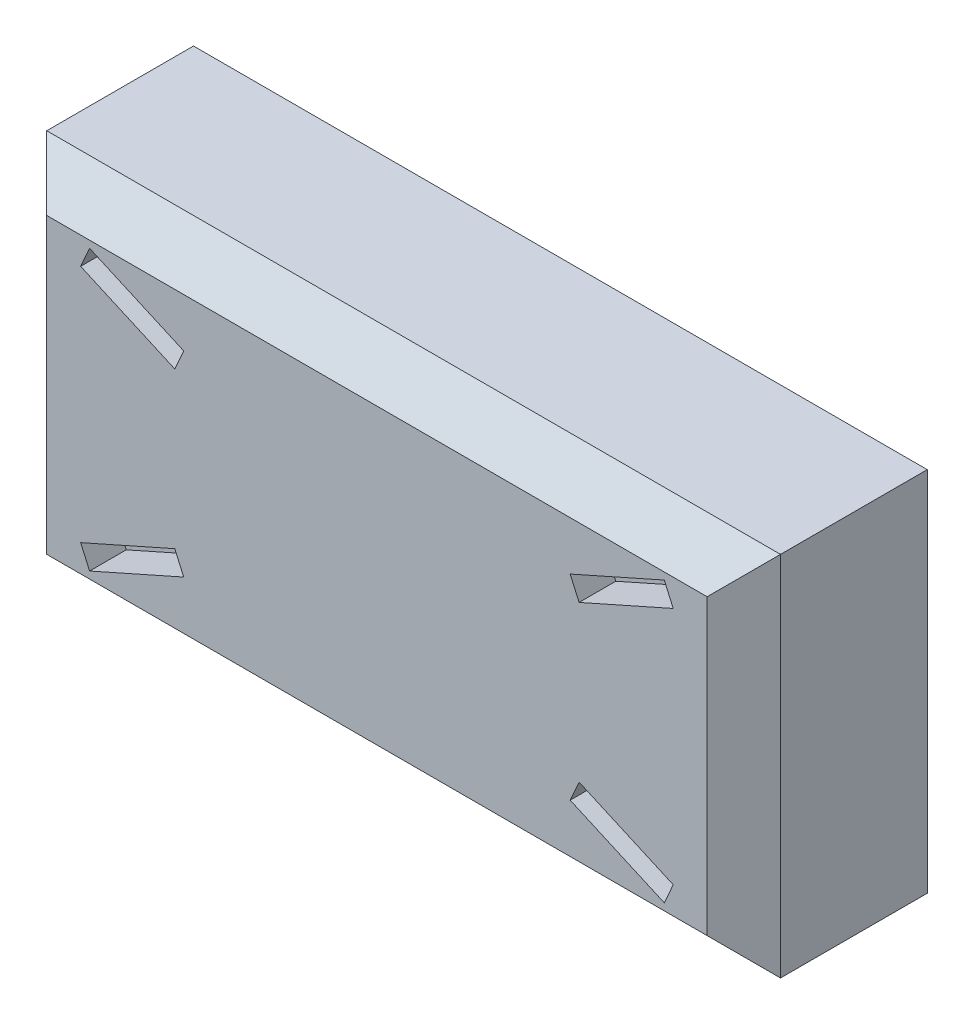
SolidWorks part; units mm, degrees
ref_plane "前视基准面" through (0, 0, 0) normal (0, 0, 1) x (1, 0, 0)
ref_plane "上视基准面" through (0, 0, 0) normal (0, 1, 0) x (1, 0, 0)
ref_plane "右视基准面" through (0, 0, 0) normal (1, 0, 0) x (0, 0, -1)
sketch "草图1" plane through (0, 0, 0) normal (0, 0, 1) x (1, 0, 0)
  line L1 (-10, -5) -> (10, -5)
  line L2 (-10, -5) -> (-10, 5)
  line L3 (-10, 5) -> (10, 5)
  line L4 (10, -5) -> (10, 5)
  line L5 (-10, -5) -> (10, 5) construction
  line L6 (-10, 5) -> (10, -5) construction
  point P0 (0, 0)
  dimension "D1" = 10
  dimension "D2" = 20
extrude "凸台-拉伸1" add sketch "草图1" along normal blind 5
chamfer "倒角1" distance 1 angle 45 4 edges at (0, -5, 5) (-10, 0, 5) (0, 5, 5) (10, 0, 5)
sketch "草图2" plane through (0, 0, 5) normal (0, 0, 1) x (1, 0, 0)
  line L0 (-9, 4) -> (9, -4) construction
  line L1 (9, 4) -> (-9, -4) construction
  line L3 (-5.2665, -2.669) -> (-5.5102, -2.1207)
  line L4 (-5.5102, -2.1207) -> (-8.0759, -3.261)
  line L5 (-8.0759, -3.261) -> (-7.8322, -3.8093)
  line L6 (-5.2665, -2.669) -> (-7.8322, -3.8093)
  line L7 (0, 0) -> (-7.2476, 0) construction
  line L8 (0, 0) -> (0, 2.3389) construction
  line L9 (-5.2665, 2.669) -> (-7.8322, 3.8093)
  line L10 (-8.0759, 3.261) -> (-7.8322, 3.8093)
  line L11 (-5.5102, 2.1207) -> (-8.0759, 3.261)
  line L12 (-5.2665, 2.669) -> (-5.5102, 2.1207)
  line L13 (5.2665, 2.669) -> (5.5102, 2.1207)
  line L14 (5.5102, 2.1207) -> (8.0759, 3.261)
  line L15 (8.0759, 3.261) -> (7.8322, 3.8093)
  line L16 (5.2665, 2.669) -> (7.8322, 3.8093)
  line L17 (5.2665, -2.669) -> (7.8322, -3.8093)
  line L18 (8.0759, -3.261) -> (7.8322, -3.8093)
  line L19 (5.5102, -2.1207) -> (8.0759, -3.261)
  line L20 (5.2665, -2.669) -> (5.5102, -2.1207)
  point P14 (-7.954, -3.5351)
  point P15 (-5.3883, -2.3948)
  point P23 (-5.3883, 2.3948)
  point P24 (-7.954, 3.5351)
  point P33 (7.954, 3.5351)
  point P34 (5.3883, 2.3948)
  point P35 (5.3883, -2.3948)
  point P36 (7.954, -3.5351)
  dimension "D1" = 0.3
extrude "切除-拉伸1" cut sketch "草图2" against normal blind 1
